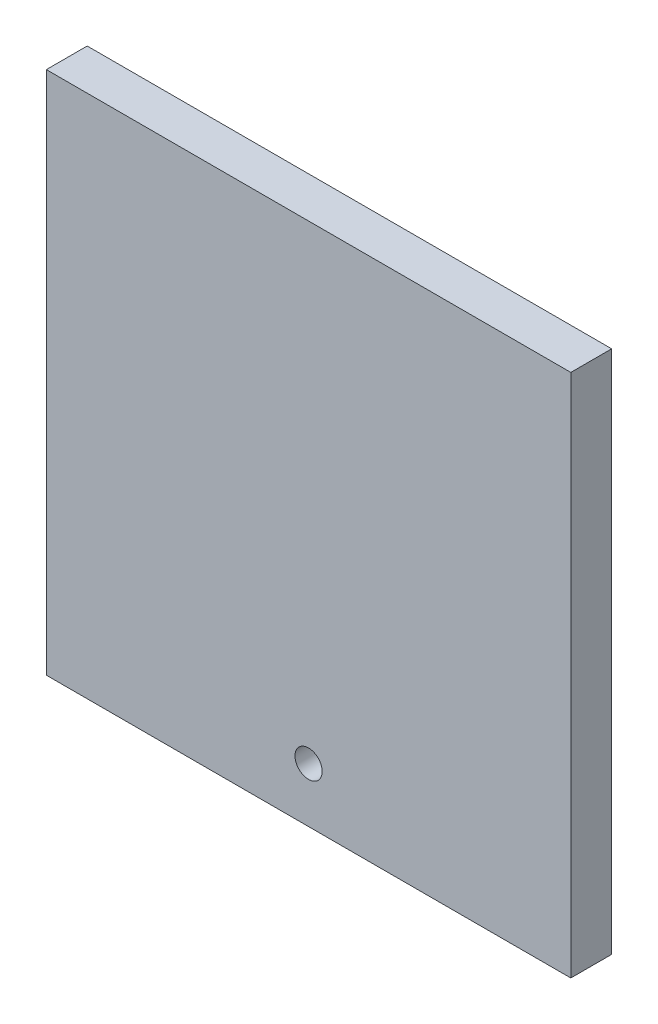
SolidWorks part; units mm, degrees
material "Maple"
ref_plane "Front Plane" through (0, 0, 0) normal (0, 0, 1) x (1, 0, 0)
ref_plane "Top Plane" through (0, 0, 0) normal (0, 1, 0) x (1, 0, 0)
ref_plane "Right Plane" through (0, 0, 0) normal (1, 0, 0) x (0, 0, -1)
sketch "Sketch1" plane through (0, 0, 0) normal (0, 0, 1) x (1, 0, 0)
  line L1 (-38.5, -38.5) -> (38.5, -38.5)
  line L2 (-38.5, -38.5) -> (-38.5, 38.5)
  line L3 (-38.5, 38.5) -> (38.5, 38.5)
  line L4 (38.5, -38.5) -> (38.5, 38.5)
  line L5 (-38.5, -38.5) -> (38.5, 38.5) construction
  line L6 (-38.5, 38.5) -> (38.5, -38.5) construction
  point P0 (0, 0)
  dimension "D1" = 77
  dimension "D2" = 77
extrude "Boss-Extrude1" add sketch "Sketch1" along normal blind 6
sketch "Sketch2" plane through (0, 0, 0) normal (0, 0, -1) x (-1, 0, 0)
  line L0 (38.5, -38.5) -> (-38.5, -38.5) construction
  circle A0 centre (0, -30.5) radius 2
  dimension "D1" = 4
  dimension "D2" = 8
extrude "Cut-Extrude1" cut sketch "Sketch2" against normal through all
